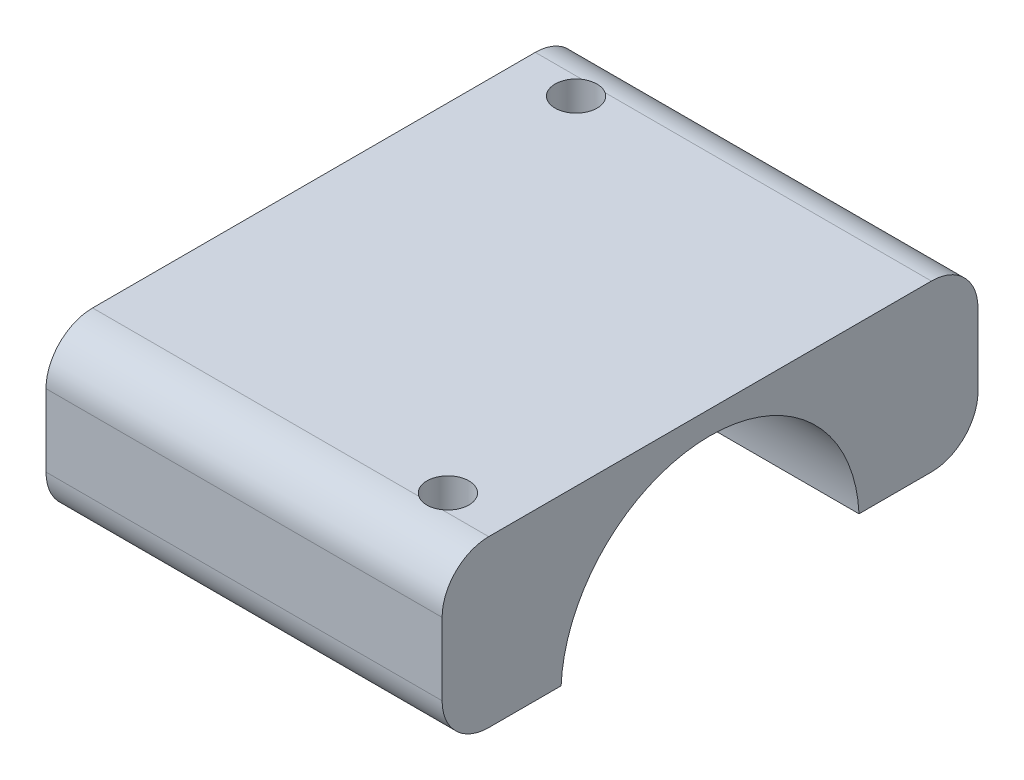
SolidWorks part; units mm, degrees
ref_plane "Front Plane" through (0, 0, 0) normal (0, 0, 1) x (1, 0, 0)
ref_plane "Top Plane" through (0, 0, 0) normal (0, 1, 0) x (1, 0, 0)
ref_plane "Right Plane" through (0, 0, 0) normal (1, 0, 0) x (0, 0, -1)
sketch "Sketch1" plane through (0, 0, 0) normal (1, 0, 0) x (0, 0, -1)
  line L0 (-19, 0.6) -> (19, 0.6)
  line L1 (23, 4.6) -> (23, 10.8)
  line L2 (19, 14.8) -> (-19, 14.8)
  line L3 (-23, 10.8) -> (-23, 4.6)
  arc A0 (19, 0.6) -> (23, 4.6) centre (19, 4.6) ccw
  arc A1 (23, 10.8) -> (19, 14.8) centre (19, 10.8) ccw
  arc A2 (-19, 14.8) -> (-23, 10.8) centre (-19, 10.8) ccw
  arc A3 (-23, 4.6) -> (-19, 0.6) centre (-19, 4.6) ccw
extrude "Boss-Extrude1" add sketch "Sketch1" along normal mid plane 34
sketch "Sketch2" plane through (0, 0, 0) normal (1, 0, 0) x (0, 0, -1)
  circle A0 centre (0, 0) radius 12.8
extrude "Cut-Extrude1" cut sketch "Sketch2" against normal through all and the other way through all
ref_plane "Plane1" through (0, 0.6, 0) normal (0, 1, 0) x (1, 0, 0)
sketch "Sketch3" plane through (0, 0.6, 0) normal (0, 1, 0) x (1, 0, 0)
  circle A0 centre (12, -17.5) radius 1.8
  circle A1 centre (-12, 17.5) radius 1.8
extrude "Cut-Extrude2" cut sketch "Sketch3" along normal blind 14.8
